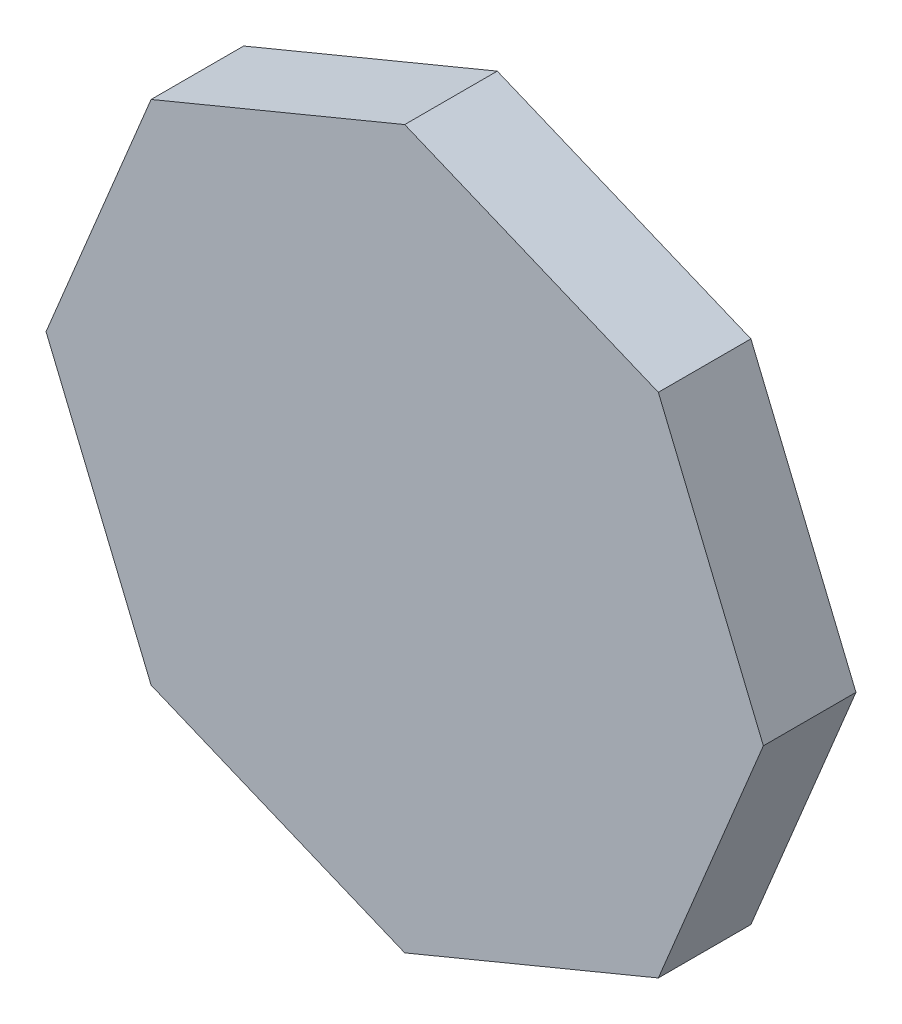
SolidWorks part; units mm, degrees
ref_plane "Front Plane" through (0, 0, 0) normal (0, 0, 1) x (1, 0, 0)
ref_plane "Top Plane" through (0, 0, 0) normal (0, 1, 0) x (1, 0, 0)
ref_plane "Right Plane" through (0, 0, 0) normal (1, 0, 0) x (0, 0, -1)
sketch "Sketch1" plane through (0, 0, 0) normal (0, 0, 1) x (1, 0, 0)
  line L1 (30.3467, 0) -> (21.267, 21.9203)
  line L2 (21.267, 21.9203) -> (-0.6533, 31)
  line L3 (-0.6533, 31) -> (-22.5736, 21.9203)
  line L4 (-22.5736, 21.9203) -> (-31.6533, 0)
  line L5 (-31.6533, 0) -> (-22.5736, -21.9203)
  line L6 (-22.5736, -21.9203) -> (-0.6533, -31)
  line L7 (-0.6533, -31) -> (21.267, -21.9203)
  line L8 (21.267, -21.9203) -> (30.3467, 0)
  circle A0 centre (-0.6533, 0) radius 28.6403 construction
  circle A1 centre (-0.6533, 0) radius 31 construction
  dimension "D1" = 31
extrude "Boss-Extrude1" add sketch "Sketch1" along normal blind 8
